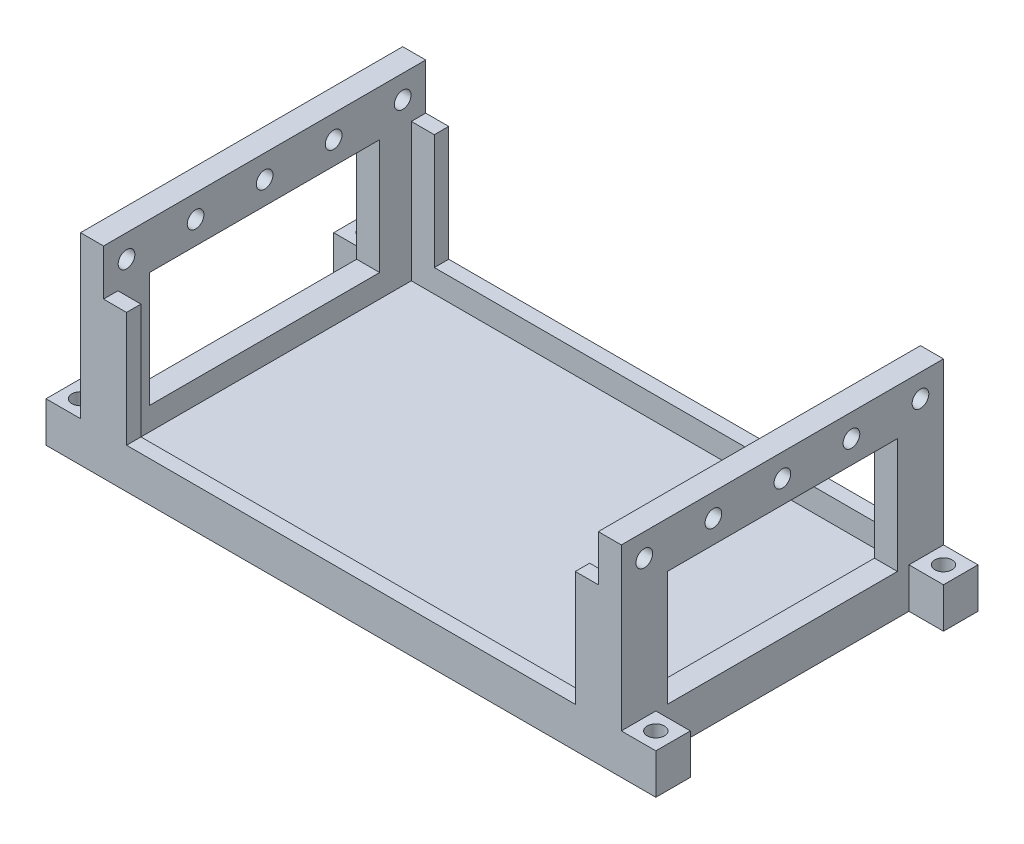
SolidWorks part; units mm, degrees
ref_plane "Front Plane" through (0, 0, 0) normal (0, 0, 1) x (1, 0, 0)
ref_plane "Top Plane" through (0, 0, 0) normal (0, 1, 0) x (1, 0, 0)
ref_plane "Right Plane" through (0, 0, 0) normal (1, 0, 0) x (0, 0, -1)
sketch "Sketch1" plane through (0, 0, 0) normal (0, 1, 0) x (1, 0, 0)
  line L0 (47, -944) -> (47, 49056) construction
  line L1 (0, 0) -> (94, 0)
  line L2 (0, 6) -> (0, 50)
  line L3 (0, 56) -> (94, 56)
  line L4 (94, 6) -> (94, 50)
  line L5 (0, 56) -> (-6, 56)
  line L7 (0, 50) -> (-6, 50)
  line L8 (-6, 56) -> (-6, 50)
  line L9 (-1000, 28) -> (49000, 28) construction
  line L10 (94, 50) -> (100, 50)
  line L11 (100, 56) -> (100, 50)
  line L12 (94, 56) -> (100, 56)
  line L14 (94, 0) -> (100, 0)
  line L15 (100, 0) -> (100, 6)
  line L16 (94, 6) -> (100, 6)
  line L18 (0, 6) -> (-6, 6)
  line L19 (-6, 0) -> (-6, 6)
  line L20 (0, 0) -> (-6, 0)
  circle A0 centre (-3, 53) radius 1.5
  circle A1 centre (97, 53) radius 1.5
  circle A2 centre (97, 3) radius 1.5
  circle A3 centre (-3, 3) radius 1.5
  point P11 (-3, 50)
  point P13 (-6, 53)
  point P17 (47, 56)
  point P18 (0, 28)
  dimension "D5" = 3
  dimension "D1" = 94
  dimension "D2" = 56
  dimension "D3" = 6
  dimension "D4" = 6
  dimension "D6" = 106
extrude "Boss-Extrude1" add sketch "Sketch1" along normal blind 3
sketch "Sketch2" plane through (0, 3, 0) normal (0, 1, 0) x (1, 0, 0)
  line L5 (4, 53.5) -> (90, 53.5)
  line L6 (4, 53.5) -> (4, 2.5)
  line L7 (4, 2.5) -> (90, 2.5)
  line L8 (0, 50) -> (0, 6)
  line L9 (-6, 0) -> (100, 0)
  line L10 (94, 6) -> (94, 50)
  line L11 (100, 56) -> (-6, 56)
  line L12 (0, 50) -> (0, 6)
  line L13 (-6, 0) -> (100, 0)
  line L14 (94, 6) -> (94, 50)
  line L15 (100, 56) -> (-6, 56)
  line L16 (90, 53.5) -> (90, 2.5)
  line L28 (100, 0) -> (100, 6)
  line L29 (100, 0) -> (100, 6)
  line L30 (100, 6) -> (94, 6)
  line L31 (100, 6) -> (94, 6)
  line L32 (94, 50) -> (100, 50)
  line L33 (94, 50) -> (100, 50)
  line L34 (100, 50) -> (100, 56)
  line L35 (100, 50) -> (100, 56)
  line L36 (-6, 56) -> (-6, 50)
  line L37 (-6, 56) -> (-6, 50)
  line L38 (-6, 50) -> (0, 50)
  line L39 (-6, 50) -> (0, 50)
  line L40 (0, 6) -> (-6, 6)
  line L41 (0, 6) -> (-6, 6)
  line L42 (-6, 6) -> (-6, 0)
  line L43 (-6, 6) -> (-6, 0)
  circle A0 centre (-3, 53) radius 1.5 construction
  circle A1 centre (-3, 53) radius 1.5
  circle A2 centre (97, 53) radius 1.5 construction
  circle A3 centre (97, 3) radius 1.5 construction
  circle A4 centre (-3, 3) radius 1.5 construction
  circle A5 centre (97, 53) radius 1.5
  circle A6 centre (97, 3) radius 1.5
  circle A7 centre (-3, 3) radius 1.5
  dimension "D2" = 2.5
  dimension "D3" = 4
  dimension "D4" = 4
  dimension "D5" = 2.5
  dimension "D1" = 0
extrude "Boss-Extrude2" add sketch "Sketch2" along normal blind 4
sketch "Sketch3" plane through (0, 7, 0) normal (0, 1, 0) x (1, 0, 0)
  line L0 (90, 53.5) -> (4, 53.5) construction
  line L1 (0, 56) -> (8, 56)
  line L2 (0, 56) -> (0, 53.5)
  line L3 (0, 53.5) -> (8, 53.5)
  line L4 (8, 56) -> (8, 53.5)
  line L5 (4, 53.5) -> (4, 2.5) construction
  line L6 (0, 53.5) -> (4, 53.5)
  line L7 (0, 53.5) -> (0, 48)
  line L8 (0, 48) -> (4, 48)
  line L9 (4, 53.5) -> (4, 48)
  line L10 (47, -946.5) -> (47, 49053.5) construction
  line L11 (100, 56) -> (-6, 56) construction
  line L12 (-996, 28) -> (49004, 28) construction
  line L13 (94, 48) -> (90, 48)
  line L14 (90, 53.5) -> (90, 48)
  line L15 (94, 53.5) -> (90, 53.5)
  line L16 (94, 53.5) -> (94, 48)
  line L17 (94, 53.5) -> (86, 53.5)
  line L18 (86, 56) -> (86, 53.5)
  line L19 (94, 56) -> (86, 56)
  line L20 (94, 56) -> (94, 53.5)
  line L21 (94, 2.5) -> (90, 2.5)
  line L22 (90, 2.5) -> (90, 8)
  line L23 (94, 8) -> (90, 8)
  line L24 (94, 2.5) -> (94, 8)
  line L25 (94, 0) -> (94, 2.5)
  line L26 (94, 0) -> (86, 0)
  line L27 (86, 0) -> (86, 2.5)
  line L28 (94, 2.5) -> (86, 2.5)
  line L29 (0, 8) -> (4, 8)
  line L30 (4, 2.5) -> (4, 8)
  line L31 (0, 2.5) -> (4, 2.5)
  line L32 (0, 2.5) -> (0, 8)
  line L33 (0, 2.5) -> (8, 2.5)
  line L34 (8, 0) -> (8, 2.5)
  line L35 (0, 0) -> (8, 0)
  line L36 (0, 0) -> (0, 2.5)
  line L37 (100, 56) -> (-6, 56) construction
  line L38 (0, 50) -> (0, 6) construction
  point P17 (47, 56)
  point P20 (4, 28)
  line M19 (100, 56) -> (-6, 56)
  line M20 (0, 50) -> (0, 6)
  line M21 (-6, 0) -> (100, 0)
  line M22 (94, 6) -> (94, 50)
  line M23 (90, 2.5) -> (4, 2.5)
  line M24 (4, 2.5) -> (4, 53.5)
  line M25 (4, 53.5) -> (90, 53.5)
  line M26 (90, 53.5) -> (90, 2.5)
  dimension "D1" = 8
  dimension "D2" = 8
extrude "Boss-Extrude3" add sketch "Sketch3" along normal blind 20 contours L8 L3 M20 M24 | L4 L3 M19 M20 M25 | L31 L29 M20 M24 | L34 L31 M21 M23 M20 | L23 L21 M22 M26 | L27 L21 M21 M22 M23 | L15 L13 M22 M26 | L18 L15 M19 M25 M22
sketch "Sketch4" plane through (0, 27, 0) normal (0, 1, 0) x (1, 0, 0)
  line L0 (0, 0) -> (8, 0) construction
  line L1 (0, 56) -> (4, 56)
  line L2 (0, 56) -> (0, 0)
  line L3 (0, 0) -> (4, 0)
  line L4 (4, 56) -> (4, 0)
  line L5 (86, 0) -> (94, 0) construction
  line L6 (94, 56) -> (90, 56)
  line L7 (94, 56) -> (94, 0)
  line L8 (94, 0) -> (90, 0)
  line L9 (90, 56) -> (90, 0)
extrude "Boss-Extrude4" add sketch "Sketch4" along normal blind 8
sketch "Sketch5" plane through (0, 0, 0) normal (-1, 0, 0) x (0, 0, 1)
  line L0 (-48, 27) -> (-48, 35) construction
  line L2 (-56, 35) -> (0, 35) construction
  line L3 (-56, 35) -> (-56, 7) construction
  line L4 (0, 35) -> (0, 7) construction
  circle A0 centre (-52, 31) radius 1.45
  circle A1 centre (-40, 31) radius 1.45
  circle A2 centre (-28, 31) radius 1.45
  circle A3 centre (-16, 31) radius 1.45
  circle A4 centre (-4, 31) radius 1.45
  point P9 (-48, 31)
  dimension "D1" = 2.9
  dimension "D2" = 4
  dimension "D4" = 4
  dimension "D3" = 5
extrude "Cut-Extrude1" cut sketch "Sketch5" against normal through all
